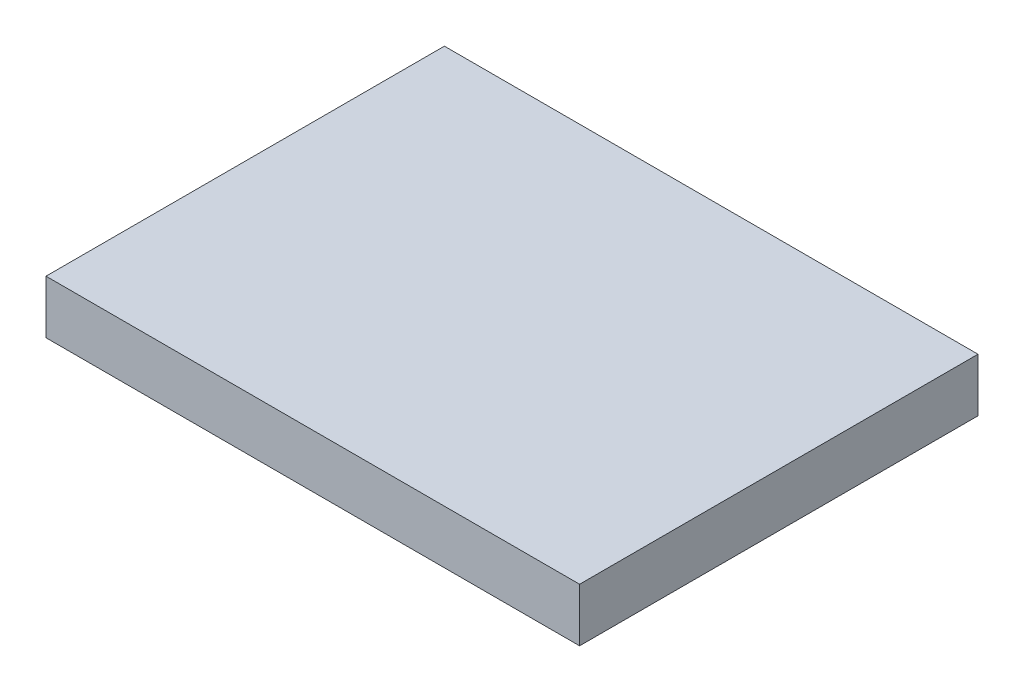
SolidWorks part; units mm, degrees
ref_plane "Front Plane" through (0, 0, 0) normal (0, 0, 1) x (1, 0, 0)
ref_plane "Top Plane" through (0, 0, 0) normal (0, 1, 0) x (1, 0, 0)
ref_plane "Right Plane" through (0, 0, 0) normal (1, 0, 0) x (0, 0, -1)
sketch "Sketch1" plane through (0, 0, 0) normal (0, 1, 0) x (1, 0, 0)
  line L5 (-952.5, -711.2) -> (952.5, -711.2)
  line L6 (-952.5, -711.2) -> (-952.5, 711.2)
  line L7 (-952.5, 711.2) -> (952.5, 711.2)
  line L8 (952.5, -711.2) -> (952.5, 711.2)
  line L9 (-952.5, -711.2) -> (952.5, 711.2) construction
  line L10 (-952.5, 711.2) -> (952.5, -711.2) construction
  point P4 (0, 0)
  dimension "D3" = 1422.4
  dimension "D4" = 1905
extrude "Boss-Extrude1" add sketch "Sketch1" along normal blind 190.5 contours L6 L7 L8 L5
